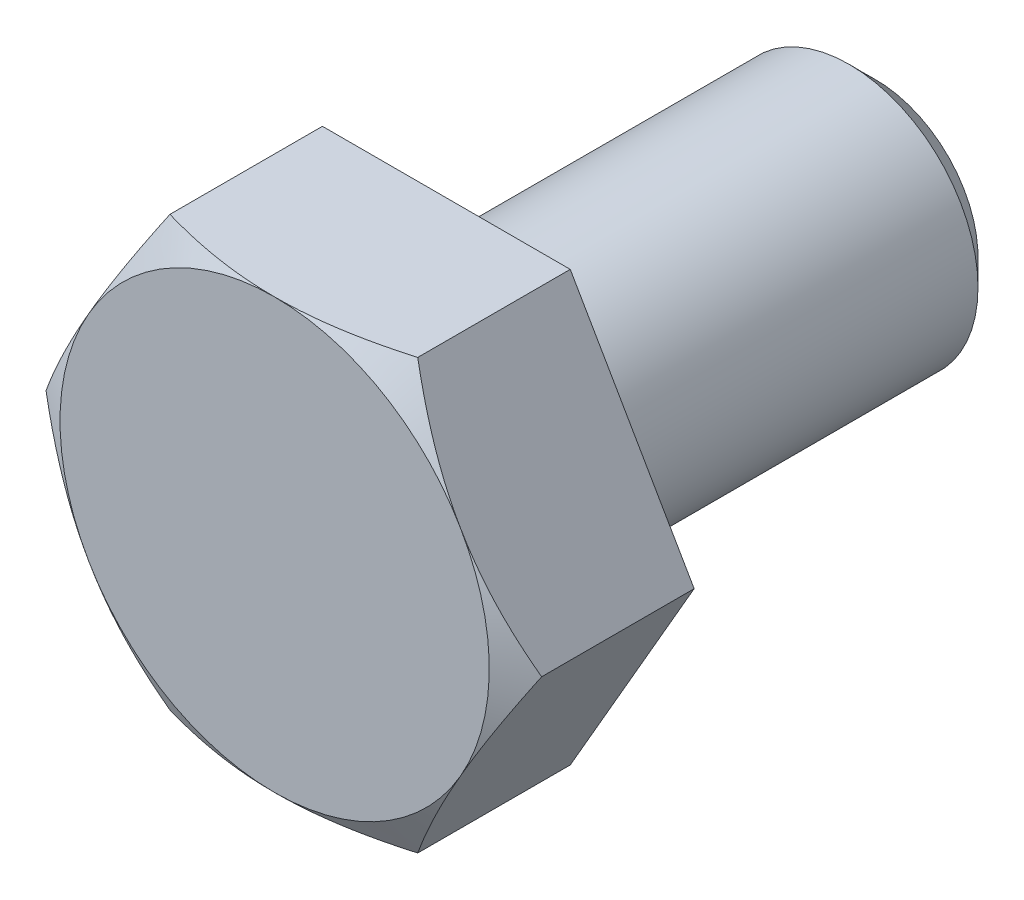
SolidWorks part; units mm, degrees
ref_plane "Plane1" through (0, 0, 0) normal (0, 0, 1) x (1, 0, 0)
ref_plane "MSC_PF1" through (0, 0, 0) normal (0, 1, 0) x (1, 0, 0)
ref_plane "Plane3" through (0, 0, 0) normal (1, 0, 0) x (0, 0, -1)
sketch "Sketch1" plane through (0, 0, 0) normal (0, 0, 1) x (1, 0, 0)
  line L0 (0, 0) -> (1, 0) construction
  line L1 (-2.8868, 5) -> (2.8868, 5)
  line L2 (-2.8868, -5) -> (2.8868, -5)
  line L3 (2.8868, 5) -> (5.7735, 0)
  line L4 (5.7735, 0) -> (2.8868, -5)
  line L5 (-2.8868, 5) -> (-5.7735, 0)
  line L6 (-5.7735, 0) -> (-2.8868, -5)
  circle A0 centre (0, 0) radius 5 construction
  dimension "P" = 1
  dimension "s" = 10
extrude "Base-Extrude" add sketch "Sketch1" along normal blind 4
sketch "Sketch5" plane through (0, 0, 0) normal (0, 1, 0) x (1, 0, 0)
  line L0 (0, 0) -> (0, -62.6881) construction
  line L1 (-5.7735, -4) -> (-5, -4)
  line L2 (-5, -4) -> (-5.7735, -3.5534)
  line L3 (-5.7735, -4) -> (-5.7735, 0) construction
  line L4 (-5.7735, -3.5534) -> (-5.7735, -4)
  dimension "D1" = 30
  dimension "D2" = 5
revolve "Cut-Revolve1" cut sketch "Sketch5" angle 360 about L0
sketch "Sketch3" plane through (0, 0, 0) normal (0, 0, -1) x (-1, 0, 0)
  circle A0 centre (0, 0) radius 3
  dimension "_d" = 6
extrude "Boss-Extrude1" add sketch "Sketch3" along normal blind 10
cosmetic thread "Cosmetic Thread1" parameters "D2"=4.7732
chamfer "Chamfer1" distance 0.6134 angle 45 1 edges at (-3, 0, -10)
fillet "Fillet1" radius 0.25 1 edges at (3, 0, 0)
equation "\"D2@Sketch5\" = \"s@Sketch1\" / 2"
equation "\"D2@Cosmetic Thread1\" = \"_d@Sketch3\" - 2 * 0.6134 * \"P@Sketch1\""
equation "\"D1@Chamfer1\" =  ( \"_d@Sketch3\" - \"D2@Cosmetic Thread1\" )  / 2"
